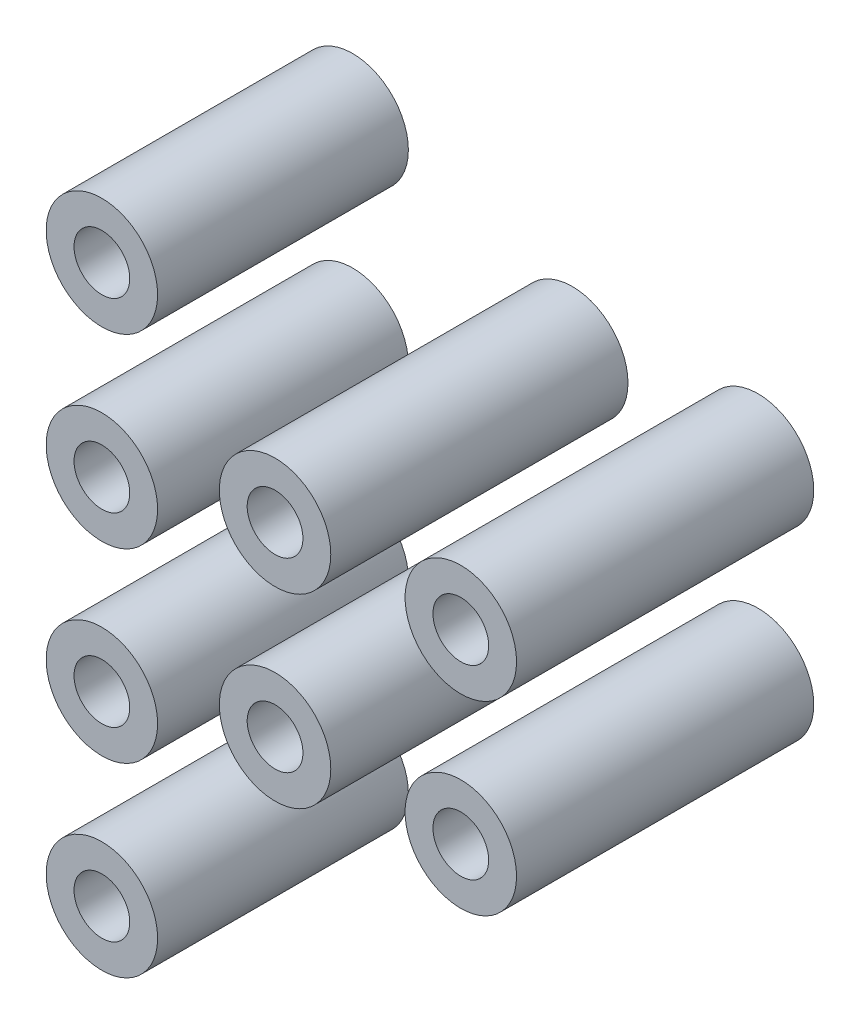
SolidWorks part; units mm, degrees
material "Plastique personnalisé"
ref_plane "Plan de face" through (0, 0, 0) normal (0, 0, 1) x (1, 0, 0)
ref_plane "Plan de dessus" through (0, 0, 0) normal (0, 1, 0) x (1, 0, 0)
ref_plane "Plan de droite" through (0, 0, 0) normal (1, 0, 0) x (0, 0, -1)
sketch "Esquisse1" plane through (0, 0, 0) normal (0, 0, 1) x (1, 0, 0)
  circle A8 centre (10, 10) radius 3
  circle A9 centre (10, 10) radius 1.5
  circle A10 centre (20, 10) radius 3
  circle A11 centre (20, 10) radius 1.5
  circle A12 centre (10, 20) radius 3
  circle A13 centre (10, 20) radius 1.5
  circle A14 centre (20, 20) radius 3
  circle A15 centre (20, 20) radius 1.5
  circle A16 centre (0, 10) radius 3
  circle A17 centre (0, 10) radius 1.5
  circle A18 centre (10, 10) radius 3
  circle A19 centre (10, 10) radius 1.5
  circle A20 centre (0, 20) radius 3
  circle A21 centre (0, 20) radius 1.5
  circle A22 centre (10, 20) radius 3
  circle A23 centre (10, 20) radius 1.5
extrude "Boss.-Extru.1" add sketch "Esquisse1" along normal blind 16 contours A13 | A12 | A9 | A8 | A17 | A16 | A21 | A20
sketch "Esquisse2" plane through (0, 0, 0) normal (0, 0, 1) x (1, 0, 0)
  circle A0 centre (-11.823, 14.9489) radius 3
  circle A1 centre (-11.823, 14.9489) radius 1.5
  circle A2 centre (-11.823, 24.9489) radius 1.5
  circle A3 centre (-11.823, 24.9489) radius 3
  dimension "D1" = 2
extrude "Boss.-Extru.2" add sketch "Esquisse2" along normal blind 13.5 separate body
sketch "Esquisse3" plane through (0, 0, 13.5) normal (0, 0, 1) x (1, 0, 0)
  line L0 (-8.823, 24.9489) -> (-8.823, -1.5317) construction
  circle A0 centre (-11.823, 24.9489) radius 3 construction
pattern_linear "Répétition linéaire1" count 2 spacing 20 along (0, -1, 0) of "Boss.-Extru.2"
